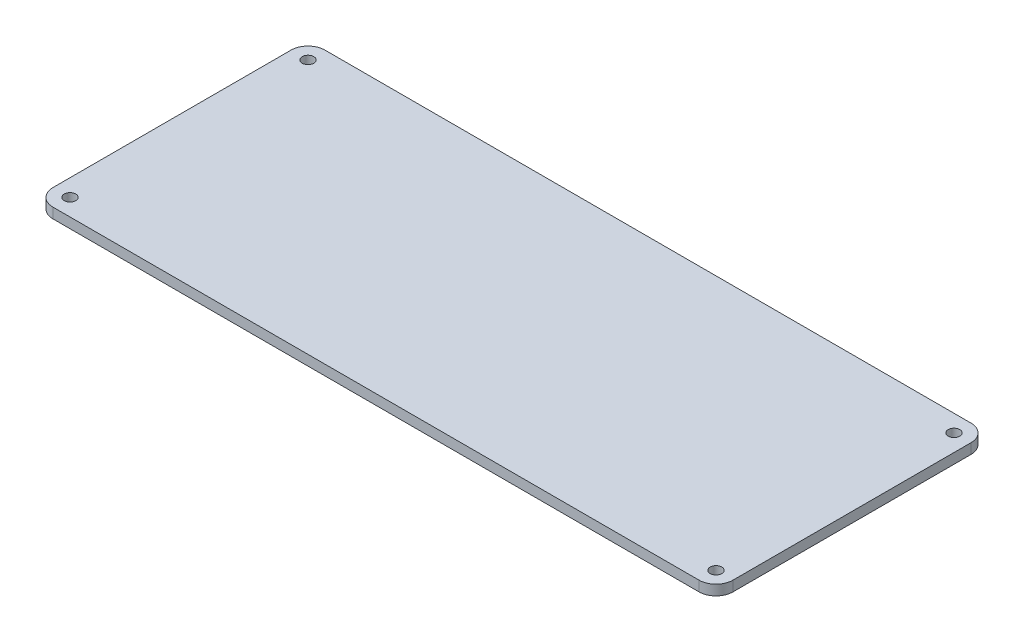
SolidWorks part; units mm, degrees
ref_plane "Front" through (0, 0, 0) normal (0, 0, 1) x (1, 0, 0)
ref_plane "Top" through (0, 0, 0) normal (0, 1, 0) x (1, 0, 0)
ref_plane "Right" through (0, 0, 0) normal (1, 0, 0) x (0, 0, -1)
sketch "Esquisse1" plane through (0, 0, 0) normal (0, 1, 0) x (1, 0, 0)
  line L1 (0, 0) -> (200, 0)
  line L2 (0, 0) -> (0, 80)
  line L3 (0, 80) -> (200, 80)
  line L4 (200, 0) -> (200, 80)
  dimension "D1" = 200
  dimension "D2" = 80
extrude "Boss.-Extru.1" add sketch "Esquisse1" along normal blind 3
fillet "Congé1" radius 5 4 edges at (0, 1.5, -80) (0, 1.5, 0) (200, 1.5, -80) (200, 1.5, 0)
sketch "Esquisse2" plane through (0, 3, 0) normal (0, 1, 0) x (1, 0, 0)
  line L0 (0, 75) -> (0, 5) construction
  line L1 (195, 80) -> (5, 80) construction
  line L2 (5, 0) -> (195, 0) construction
  line L3 (200, 5) -> (200, 75) construction
  circle A0 centre (5, 75) radius 1
  circle A1 centre (195, 75) radius 1
  circle A2 centre (195, 5) radius 1
  circle A3 centre (5, 5) radius 1
  point P10 (0, 0)
  point P12 (0, 0)
  dimension "D9" = 2
  dimension "D10" = 2
  dimension "D11" = 2
  dimension "D12" = 2
  dimension "D1" = 5
  dimension "D2" = 5
  dimension "D3" = 5
  dimension "D4" = 5
  dimension "D5" = 5
  dimension "D6" = 5
  dimension "D7" = 5
  dimension "D8" = 5
extrude "Enlèv. mat.-Extru.1" cut sketch "Esquisse2" against normal through all
hole_wizard "Dégagement M31" positions "Esquisse3" profile "Esquisse4" hole size "M3" standard "ISO"
sketch "Esquisse3" plane through (0, 3, 0) normal (0, 1, 0) x (1, 0, 0)
  point P0 (195, 5)
  point P3 (5, 5)
  point P6 (5, 75)
  point P9 (195, 75)
sketch "Esquisse4" plane through (195, 3, -5) normal (1, 0, 0) x (0, 0, 1)
  line L0 (0, 0) -> (0, 11.0215)
  line L1 (0, 11.0215) -> (1.7, 10)
  line L2 (1.7, 10) -> (1.7, 0)
  line L5 (1.7, 0) -> (0, 0)
  line L10 (0, 11.0215) -> (-1.7, 10) construction
  line L11 (0, -6.35) -> (0, 107.95) construction
  dimension "Diamètre du perçage" = 3.4
  dimension "Profondeur du perçage" = 10
  dimension "Angle de pointe" = 118
